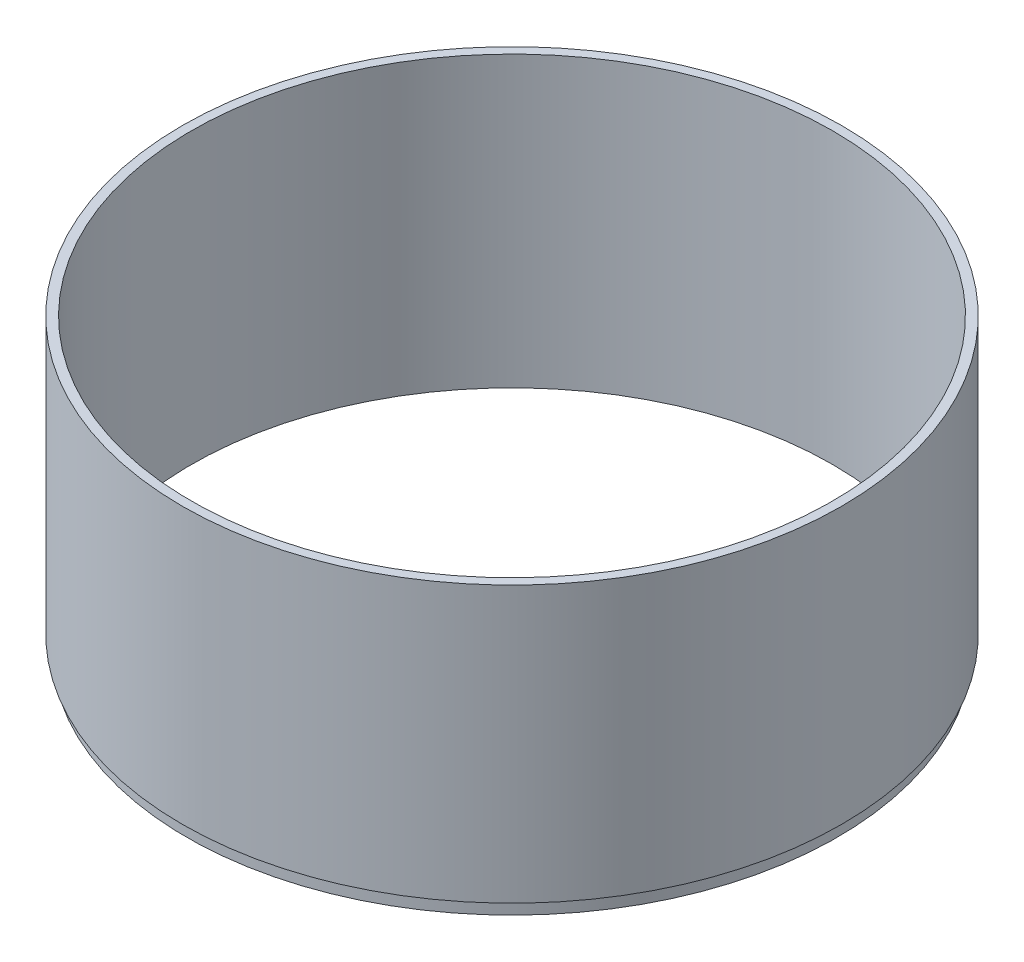
SolidWorks part; units mm, degrees
material "Silica Phenolic"
ref_plane "Piano frontale" through (0, 0, 0) normal (0, 0, 1) x (1, 0, 0)
ref_plane "Piano superiore" through (0, 0, 0) normal (0, 1, 0) x (1, 0, 0)
ref_plane "Piano destro" through (0, 0, 0) normal (1, 0, 0) x (0, 0, -1)
sketch "Schizzo1" plane through (0, 0, 0) normal (0, 0, 1) x (1, 0, 0)
  line L0 (-71, 3) -> (-71, 0)
  line L2 (-73, 3) -> (-73, 64)
  line L3 (-73, 64) -> (-71, 64)
  line L8 (0, 0) -> (0, 47.1479) construction
  line L9 (-71, 0) -> (-72, 0)
  line L10 (-72, 0) -> (-72, 3)
  line L11 (-72, 3) -> (-73, 3)
  line L12 (-71, 3) -> (-71, 64)
  point P2 (-71, 60.7089)
  point P6 (-72, 53.0352)
  point P11 (0, 0)
  point P15 (-71, 62.7923)
  point P16 (-71, 64)
  point P17 (-71, 63.7432)
  point P19 (-70.1043, 53)
  dimension "D1" = 146
  dimension "D3" = 3
  dimension "D4" = 1
  dimension "D5" = 1
  dimension "D6" = 64
revolve "Rivoluzione1" add sketch "Schizzo1" angle 360 about L8
